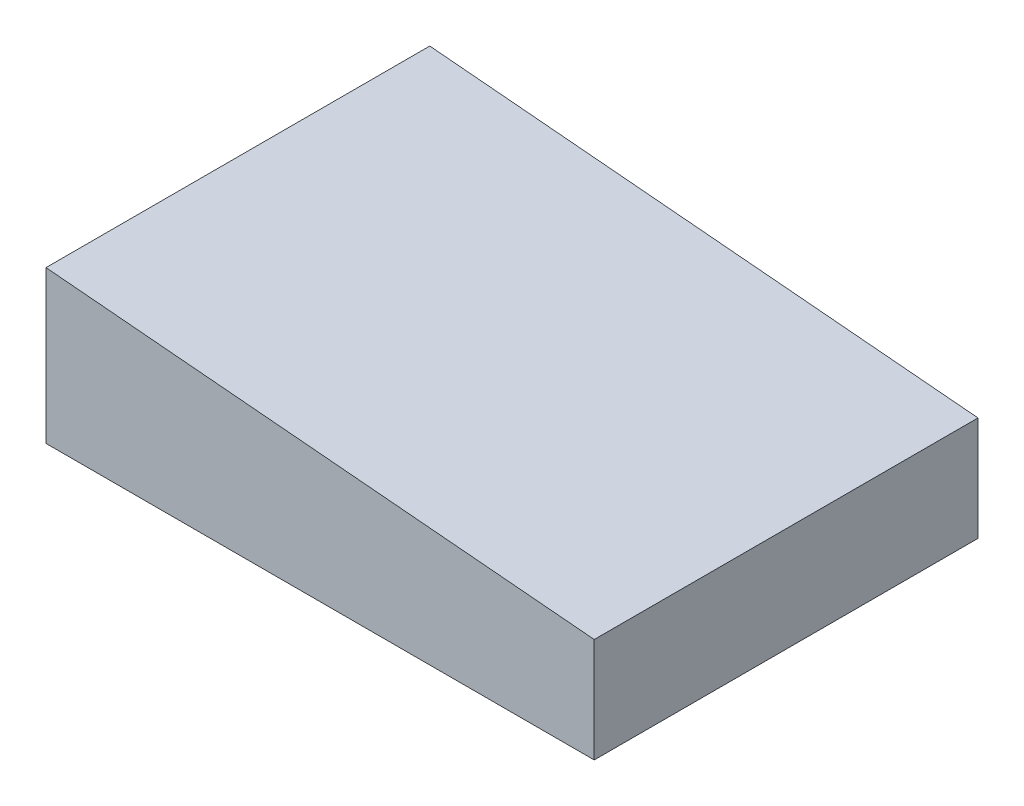
SolidWorks part; units mm, degrees
ref_plane "Front Plane" through (0, 0, 0) normal (0, 0, 1) x (1, 0, 0)
ref_plane "Top Plane" through (0, 0, 0) normal (0, 1, 0) x (1, 0, 0)
ref_plane "Right Plane" through (0, 0, 0) normal (1, 0, 0) x (0, 0, -1)
sketch "Sketch1" plane through (0, 0, 0) normal (0, 0, 1) x (1, 0, 0)
  line L0 (0, 0) -> (0, 27.78)
  line L1 (0, 27.78) -> (317.5269, 0)
  line L2 (317.5269, 0) -> (0, 0)
  dimension "D1" = 27.78
  dimension "D2" = 5
extrude "Boss-Extrude1" add sketch "Sketch1" along normal mid plane 70
sketch "Sketch2" plane through (0, 0, 0) normal (0, -1, 0) x (1, 0, 0)
  line L0 (0, -35) -> (317.5269, -35) construction
  line L1 (317.5269, 35) -> (100, 35)
  line L2 (317.5269, 35) -> (317.5269, -35)
  line L3 (317.5269, -35) -> (100, -35)
  line L4 (100, 35) -> (100, -35)
  line L5 (0, 35) -> (0, -35) construction
  dimension "D1" = 100
extrude "Cut-Extrude1" cut sketch "Sketch2" against normal blind 70
sketch "Sketch3" plane through (0, 0, 0) normal (0, -1, 0) x (1, 0, 0)
  line L0 (0, 35) -> (100, -35) construction
  line L1 (59.359, -28) -> (59.359, -35) construction
  line L2 (7, 28) -> (93, 28) construction
  line L3 (7, 28) -> (7, -28) construction
  line L4 (7, -28) -> (93, -28) construction
  line L5 (93, 28) -> (93, -28) construction
  line L6 (7, 28) -> (93, -28) construction
  line L7 (7, -28) -> (93, 28) construction
  line L8 (0, -35) -> (100, -35) construction
  line L9 (93, -6.2222) -> (100, -6.2222) construction
  line L10 (100, 35) -> (100, -35) construction
  circle A0 centre (7, 28) radius 1.5
  circle A1 centre (93, 28) radius 1.5
  circle A2 centre (7, -28) radius 1.5
  circle A3 centre (93, -28) radius 1.5
  point P4 (50, 0)
  dimension "D2" = 3
  dimension "D1" = 7
extrude "Cut-Extrude2" cut sketch "Sketch3" against normal offset from surface (24.0249 mm away) 3
